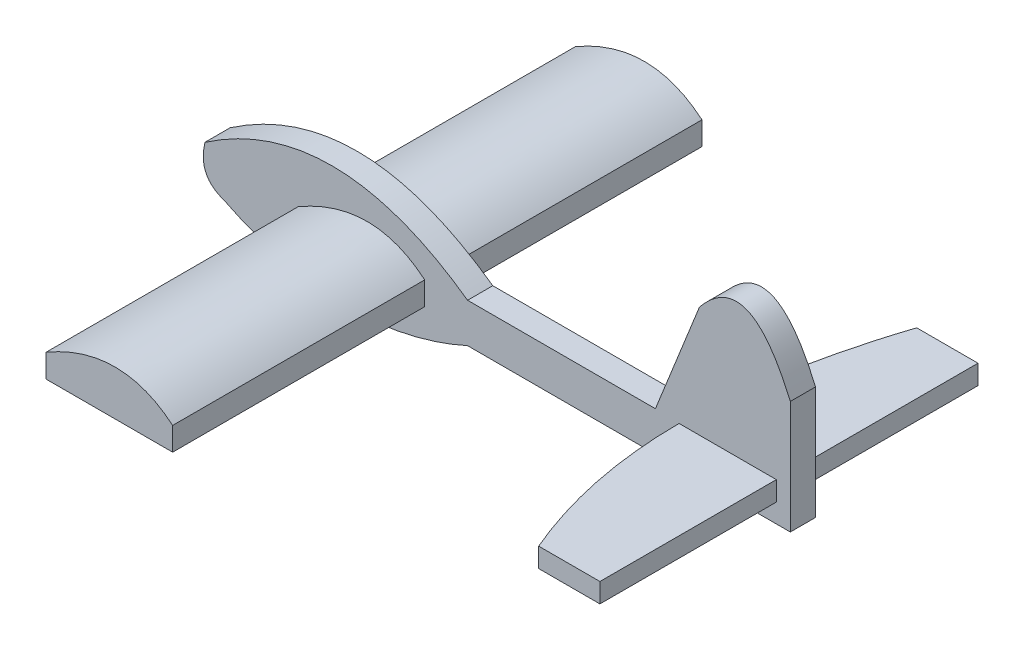
SolidWorks part; units mm, degrees
ref_plane "Front Plane" through (0, 0, 0) normal (0, 0, 1) x (1, 0, 0)
ref_plane "Top Plane" through (0, 0, 0) normal (0, 1, 0) x (1, 0, 0)
ref_plane "Right Plane" through (0, 0, 0) normal (1, 0, 0) x (0, 0, -1)
sketch "Sketch1" plane through (0, 0, 0) normal (0, 0, 1) x (1, 0, 0)
  line L0 (57.1818, 10.7102) -> (131.7035, 10.7102)
  line L1 (57.1818, -4.9013) -> (185.2241, -4.9013)
  line L2 (131.7035, 10.7102) -> (149.1861, 54.3925)
  line L3 (185.2241, 39.9692) -> (185.2241, -4.9013)
  spline S0 degree 2 poles (-47.0162, 12.8886) (4.654, 48.22) (57.1818, 10.7102) knots 0 0 0 1 1 1
  spline S1 degree 2 poles (-47.0162, 12.8886) (-49.929, 0.4603) (-39.755, -3.086) knots 0 0 0 1 1 1
  spline S2 degree 2 poles (-39.755, -3.086) (8.1723, -26.9136) (57.1818, -4.9013) knots 0 0 0 1 1 1
  spline S3 degree 2 poles (149.1861, 54.3925) (168.8272, 78.3845) (185.2241, 39.9692) knots 0 0 0 1 1 1
extrude "Boss-Extrude1" add sketch "Sketch1" along normal blind 10
sketch "Sketch2" plane through (0, 0, 0) normal (0, 0, 1) x (1, 0, 0)
  line L0 (-10.0726, 9.2134) -> (-10.0726, 0)
  line L1 (-10.0726, 0) -> (40.1772, 0)
  line L2 (40.1772, 0) -> (40.1772, 9.2134)
  line L3 (40.1772, 9.2134) -> (-10.0726, 9.2134)
extrude "Boss-Extrude4" add sketch "Sketch2" along normal blind 110 and the other way blind 100
sketch "Sketch3" plane through (0, 0, -100) normal (0, 0, -1) x (-1, 0, 0)
  line L4 (10.0726, 9.2134) -> (-40.1772, 9.2134)
  line L5 (-40.1772, 9.2134) -> (-40.1772, 0)
  line L6 (-40.1772, 0) -> (10.0726, 0)
  line L7 (10.0726, 0) -> (10.0726, 9.2134)
  line L9 (-40.1772, 9.2134) -> (-40.1772, 0)
  line L10 (-40.1772, 0) -> (10.0726, 0)
  line L11 (10.0726, 0) -> (10.0726, 9.2134)
  spline S0 degree 2 poles (-40.1772, 9.2134) (-19.5228, 26.526) (10.0726, 9.2134) knots 0 0 0 1 1 1
  point P2 (0, 0)
  point P4 (-33.8378, 13.5961)
  dimension "D1" = 0
extrude "Boss-Extrude6" add sketch "Sketch3" against normal blind 210 contours L9 L10 L11 S0
sketch "Sketch6" plane through (0, 0, 10) normal (0, 0, 1) x (1, 0, 0)
  line L1 (141.1007, 10.339) -> (179.6863, 10.339)
  line L2 (141.1007, 10.339) -> (141.1007, 2.6219)
  line L3 (141.1007, 2.6219) -> (179.6863, 2.6219)
  line L4 (179.6863, 10.339) -> (179.6863, 2.6219)
extrude "Boss-Extrude9" add sketch "Sketch6" along normal blind 70 and the other way blind 80 contours L2 L1 L4 L3
sketch "Sketch7" plane through (0, 10.339, 0) normal (0, 1, 0) x (1, 0, 0)
  line L0 (141.1007, -80) -> (179.6863, -80) construction
  line L5 (179.6863, -80) -> (179.6863, -10)
  line L6 (179.6863, -10) -> (141.1007, -10)
  line L7 (141.1007, -10) -> (141.1007, -80)
  line L8 (141.1007, -80) -> (179.6863, -80)
  line L11 (141.1007, -10) -> (141.1007, -80)
  line L12 (141.1007, -80) -> (155.3742, -80)
  spline S0 degree 2 poles (141.1007, -10) (141.1561, -46.5548) (155.3742, -80) knots 0 0 0 1 1 1
  point P2 (0, 0)
  point P4 (143.4183, -48.9838)
  point P5 (0, 0)
  point P9 (0, 0)
  point P10 (0, 0)
  point P11 (0, 0)
  point P12 (147.966, -47.7767)
  point P13 (0, 0)
  point P14 (0, 0)
  point P15 (144.8256, -50.1781)
  point P16 (0, 0)
  point P17 (0, 0)
  point P18 (0, 0)
  point P19 (0, 0)
  point P20 (0, 0)
  point P21 (148.1088, -49.4052)
  point P22 (0, 0)
  point P23 (0, 0)
  point P24 (145.8273, -50.9262)
  dimension "D1" = 0
extrude "Cut-Extrude1" cut sketch "Sketch7" against normal blind 70
sketch "Sketch10" plane through (0, 10.339, 0) normal (0, 1, 0) x (1, 0, 0)
  line L0 (141.1007, 70) -> (179.6863, 70) construction
  spline S0 degree 2 poles (141.1007, 0) (144.1111, 35.9017) (155.3742, 70) knots 0 0 0 1 1 1
extrude "Cut-Extrude2" cut sketch "Sketch10" against normal through all and the other way through all
